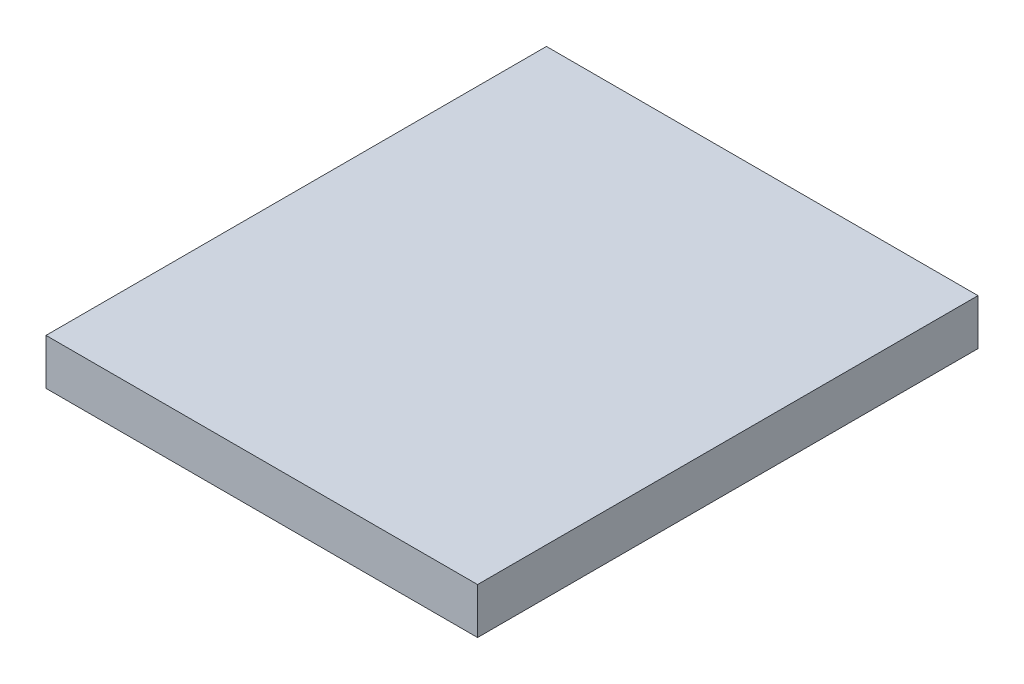
SolidWorks part; units mm, degrees
ref_plane "Front Plane" through (0, 0, 0) normal (0, 0, 1) x (1, 0, 0)
ref_plane "Top Plane" through (0, 0, 0) normal (0, 1, 0) x (1, 0, 0)
ref_plane "Right Plane" through (0, 0, 0) normal (1, 0, 0) x (0, 0, -1)
sketch "Sketch1" plane through (0, 0, 0) normal (0, 1, 0) x (1, 0, 0)
  line L1 (-47, -54.5) -> (47, -54.5)
  line L2 (-47, -54.5) -> (-47, 54.5)
  line L3 (-47, 54.5) -> (47, 54.5)
  line L4 (47, -54.5) -> (47, 54.5)
  line L5 (-47, -54.5) -> (47, 54.5) construction
  line L6 (-47, 54.5) -> (47, -54.5) construction
  point P0 (0, 0)
  dimension "D1" = 109
  dimension "D2" = 94
extrude "Boss-Extrude1" add sketch "Sketch1" along normal blind 10
shell "Shell1" thickness 2
